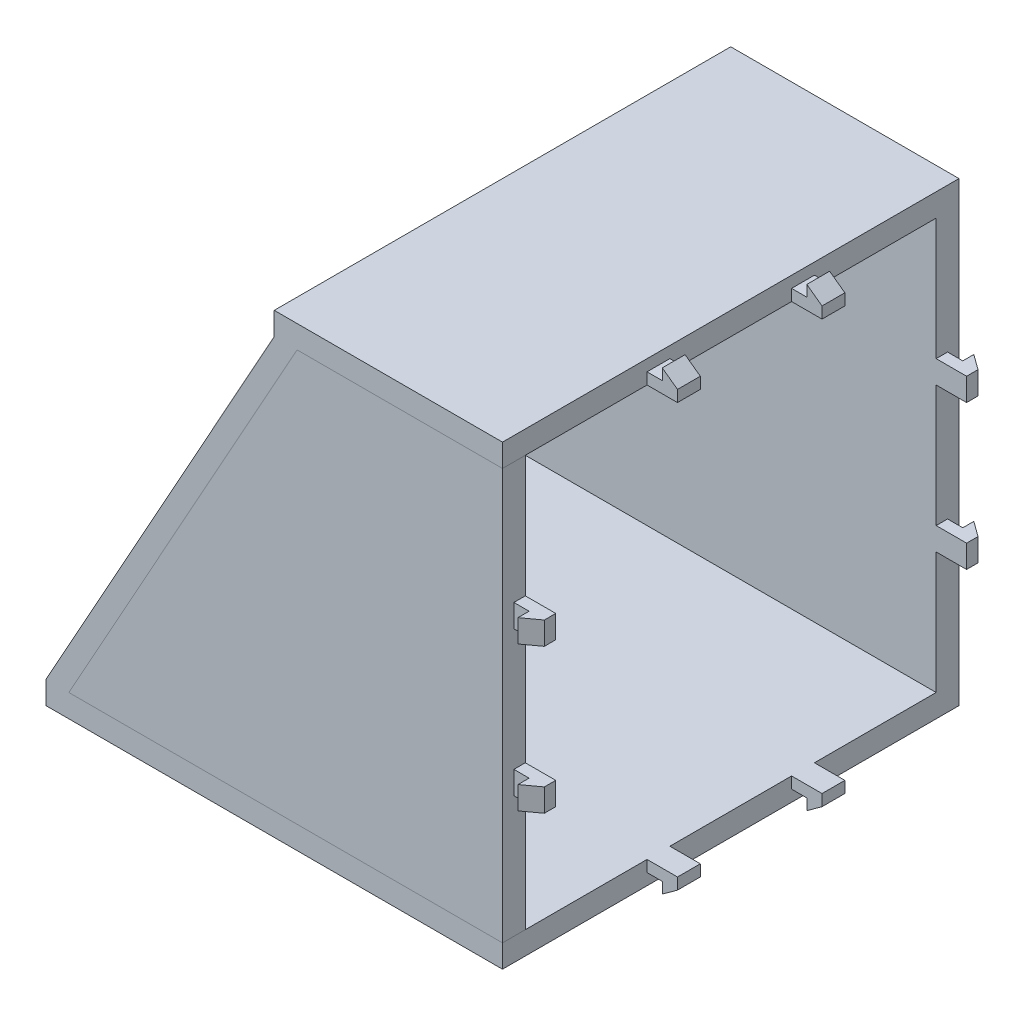
SolidWorks part; units mm, degrees
ref_plane "前视基准面" through (0, 0, 0) normal (0, 0, 1) x (1, 0, 0)
ref_plane "上视基准面" through (0, 0, 0) normal (0, 1, 0) x (1, 0, 0)
ref_plane "右视基准面" through (0, 0, 0) normal (1, 0, 0) x (0, 0, -1)
sketch "草图1" plane through (0, 0, 0) normal (0, 1, 0) x (1, 0, 0)
  line L1 (-30, 30) -> (30, 30)
  line L2 (-30, 30) -> (-30, -30)
  line L3 (-30, -30) -> (30, -30)
  line L4 (30, 30) -> (30, -30)
  line L5 (-30, 30) -> (30, -30) construction
  line L6 (-30, -30) -> (30, 30) construction
  point P0 (0, 0)
  dimension "D1" = 60
  dimension "D2" = 60
extrude "凸台-拉伸1" add sketch "草图1" along normal blind 3
ref_plane "基准面1" through (0, 57, 0) normal (0, 1, 0) x (1, 0, 0)
sketch "草图2" plane through (0, 57, 0) normal (0, 1, 0) x (1, 0, 0)
  line L1 (30, 30) -> (0, 30)
  line L2 (30, 30) -> (30, -30)
  line L3 (30, -30) -> (0, -30)
  line L4 (0, 30) -> (0, -30)
  dimension "D1" = 30
extrude "凸台-拉伸2" add sketch "草图2" along normal blind 3 separate body
sketch "草图4" plane through (0, 3, 0) normal (0, 1, 0) x (1, 0, 0)
  line L0 (-30, -30) -> (30, -30) construction
  line L1 (-30, 30) -> (-27, 30)
  line L2 (-30, 30) -> (-30, -30)
  line L3 (-30, -30) -> (-27, -30)
  line L4 (-27, 30) -> (-27, -30)
  dimension "D1" = 3
sketch "草图5" plane through (0, 57, 0) normal (0, -1, 0) x (1, 0, 0)
  line L0 (30, -30) -> (0, -30) construction
  line L1 (0, 30) -> (3, 30)
  line L2 (0, 30) -> (0, -30)
  line L3 (0, -30) -> (3, -30)
  line L4 (3, 30) -> (3, -30)
  dimension "D1" = 3
loft "放样1" add profiles "草图5", "草图4"
sketch "草图6" plane through (0, 0, 30) normal (0, 0, 1) x (1, 0, 0)
  line L1 (30, 57) -> (3, 57)
  line L2 (3, 57) -> (-27, 3)
  line L3 (-27, 3) -> (30, 3)
  line L4 (30, 3) -> (30, 57)
extrude "凸台-拉伸3" add sketch "草图6" against normal blind 3 separate body
sketch "草图7" plane through (0, 0, -30) normal (0, 0, -1) x (-1, 0, 0)
  line L0 (-30, 57) -> (-3, 57)
  line L1 (-30, 60) -> (-30, 57) construction
  line L2 (-3, 57) -> (27, 3)
  line L3 (27, 3) -> (-30, 3)
  line L4 (-30, 3) -> (-30, 57)
extrude "凸台-拉伸4" add sketch "草图7" against normal blind 3
sketch "草图9" plane through (30, 0, 0) normal (1, 0, 0) x (0, 0, -1)
  line L0 (27, 22) -> (27, 19)
  line L1 (27, 22) -> (28.5, 22)
  line L2 (28.5, 22) -> (28.5, 19)
  line L3 (27, 19) -> (28.5, 19)
  line L4 (27, 41) -> (27, 38)
  line L5 (8, 57) -> (11, 57)
  line L6 (8, 57) -> (8, 58.5)
  line L7 (8, 58.5) -> (11, 58.5)
  line L8 (11, 57) -> (11, 58.5)
  line L9 (-11, 57) -> (-8, 57)
  line L10 (-11, 57) -> (-11, 58.5)
  line L11 (-11, 58.5) -> (-8, 58.5)
  line L12 (-8, 57) -> (-8, 58.5)
  line L13 (27, 41) -> (28.5, 41)
  line L14 (28.5, 41) -> (28.5, 38)
  line L15 (27, 38) -> (28.5, 38)
  line L16 (-8, 3) -> (-11, 3)
  line L17 (-8, 3) -> (-8, 1.5)
  line L18 (-30, 57) -> (27, 57) construction
  line L19 (-8, 1.5) -> (-11, 1.5)
  line L20 (-11, 3) -> (-11, 1.5)
  line L21 (-27, 57) -> (27, 3) construction
  line L22 (-27, 3) -> (27, 3) construction
  line L23 (-27, 3) -> (-27, 57) construction
  line L24 (-27, 57) -> (27, 57) construction
  line L25 (27, 3) -> (27, 57) construction
  line L26 (11, 3) -> (8, 3)
  line L27 (11, 3) -> (11, 1.5)
  line L28 (11, 1.5) -> (8, 1.5)
  line L29 (8, 3) -> (8, 1.5)
  line L30 (-27, 38) -> (-27, 41)
  line L31 (-27, 38) -> (-28.5, 38)
  line L32 (-28.5, 38) -> (-28.5, 41)
  line L33 (-27, 41) -> (-28.5, 41)
  line L34 (-27, 19) -> (-27, 22)
  line L35 (-27, 19) -> (-28.5, 19)
  line L36 (-28.5, 19) -> (-28.5, 22)
  line L37 (-27, 22) -> (-28.5, 22)
  point P20 (0, 30)
  point P45 (0, 30)
  dimension "D1" = 3
  dimension "D2" = 16
  dimension "D3" = 3
  dimension "D4" = 16
  dimension "D5" = 1.5
  dimension "D6" = 1.5
  dimension "D7" = 4
extrude "凸台-拉伸5" add sketch "草图9" along normal blind 2
sketch "草图10" plane through (32, 0, 0) normal (1, 0, 0) x (0, 0, -1)
  line L0 (-11, 58.5) -> (-11, 57) construction
  line L1 (-11, 57) -> (-8, 57)
  line L2 (-11, 57) -> (-11, 60)
  line L3 (-11, 60) -> (-8, 60)
  line L4 (-8, 57) -> (-8, 60)
  line L6 (8, 60) -> (11, 60)
  line L7 (8, 60) -> (8, 57)
  line L8 (8, 57) -> (11, 57)
  line L9 (11, 60) -> (11, 57)
  line L33 (-27, 57) -> (27, 3) construction
  line L34 (27, 41) -> (27, 38)
  line L35 (27, 41) -> (30, 41)
  line L36 (30, 41) -> (30, 38)
  line L37 (27, 38) -> (30, 38)
  line L38 (30, 22) -> (30, 19)
  line L39 (30, 22) -> (27, 22)
  line L40 (27, 22) -> (27, 19)
  line L41 (30, 19) -> (27, 19)
  line L42 (11, 3) -> (8, 3)
  line L43 (11, 3) -> (11, 0)
  line L44 (11, 0) -> (8, 0)
  line L45 (8, 3) -> (8, 0)
  line L46 (-8, 0) -> (-11, 0)
  line L47 (-8, 0) -> (-8, 3)
  line L48 (-8, 3) -> (-11, 3)
  line L49 (-11, 0) -> (-11, 3)
  line L50 (-27, 19) -> (-27, 22)
  line L51 (-27, 19) -> (-30, 19)
  line L52 (-30, 19) -> (-30, 22)
  line L53 (-27, 22) -> (-30, 22)
  line L54 (-30, 38) -> (-30, 41)
  line L55 (-30, 38) -> (-27, 38)
  line L56 (-27, 38) -> (-27, 41)
  line L57 (-30, 41) -> (-27, 41)
  point P46 (0, 30)
  point P71 (0, 30)
  dimension "D1" = 3
  dimension "D2" = 3
  dimension "D4" = 4
extrude "凸台-拉伸6" add sketch "草图10" along normal blind 2
sketch "草图11" plane through (34, 0, 0) normal (1, 0, 0) x (0, 0, -1)
  line L0 (30, 0) -> (-30, 60) construction
  line L1 (28.5, 42.477) -> (31.5, 42.477)
  line L2 (28.5, 42.477) -> (28.5, 36.477)
  line L3 (28.5, 36.477) -> (31.5, 36.477)
  line L4 (31.5, 42.477) -> (31.5, 36.477)
  line L5 (-9.253, 30) -> (11.6115, 30) construction
  line L6 (31.5, 17.523) -> (31.5, 23.523)
  line L7 (28.5, 23.523) -> (31.5, 23.523)
  line L8 (28.5, 17.523) -> (28.5, 23.523)
  line L9 (28.5, 17.523) -> (31.5, 17.523)
  line L10 (12.477, 1.5) -> (12.477, -1.5)
  line L11 (12.477, 1.5) -> (6.477, 1.5)
  line L12 (6.477, 1.5) -> (6.477, -1.5)
  line L13 (12.477, -1.5) -> (6.477, -1.5)
  line L14 (-12.477, -1.5) -> (-6.477, -1.5)
  line L15 (-6.477, 1.5) -> (-6.477, -1.5)
  line L16 (-12.477, 1.5) -> (-6.477, 1.5)
  line L17 (-12.477, 1.5) -> (-12.477, -1.5)
  line L18 (-28.5, 17.523) -> (-31.5, 17.523)
  line L19 (-28.5, 17.523) -> (-28.5, 23.523)
  line L20 (-28.5, 23.523) -> (-31.5, 23.523)
  line L21 (-31.5, 17.523) -> (-31.5, 23.523)
  line L22 (-31.5, 42.477) -> (-31.5, 36.477)
  line L23 (-28.5, 36.477) -> (-31.5, 36.477)
  line L24 (-28.5, 42.477) -> (-28.5, 36.477)
  line L25 (-28.5, 42.477) -> (-31.5, 42.477)
  line L26 (-12.477, 58.5) -> (-12.477, 61.5)
  line L27 (-12.477, 58.5) -> (-6.477, 58.5)
  line L28 (-6.477, 58.5) -> (-6.477, 61.5)
  line L29 (-12.477, 61.5) -> (-6.477, 61.5)
  line L30 (12.477, 61.5) -> (6.477, 61.5)
  line L31 (6.477, 58.5) -> (6.477, 61.5)
  line L32 (12.477, 58.5) -> (6.477, 58.5)
  line L33 (30, 38) -> (30, 41) construction
  line L35 (12.477, 58.5) -> (12.477, 61.5)
  line L36 (27.1434, 39.477) -> (29.8566, 39.477) construction
  line L39 (30, 41) -> (27, 41) construction
  point P11 (28.5, 39.477)
  point P13 (0, 30)
  point P41 (0, 30)
  point P43 (0, 30)
  point P48 (28.5, 41)
  point P49 (31.5, 39.477)
  dimension "D1" = 6
  dimension "D2" = 4
  dimension "D4" = 3
  dimension "D5" = 1.5
extrude "切除-拉伸2" cut sketch "草图11" against normal blind 7 draft 36
